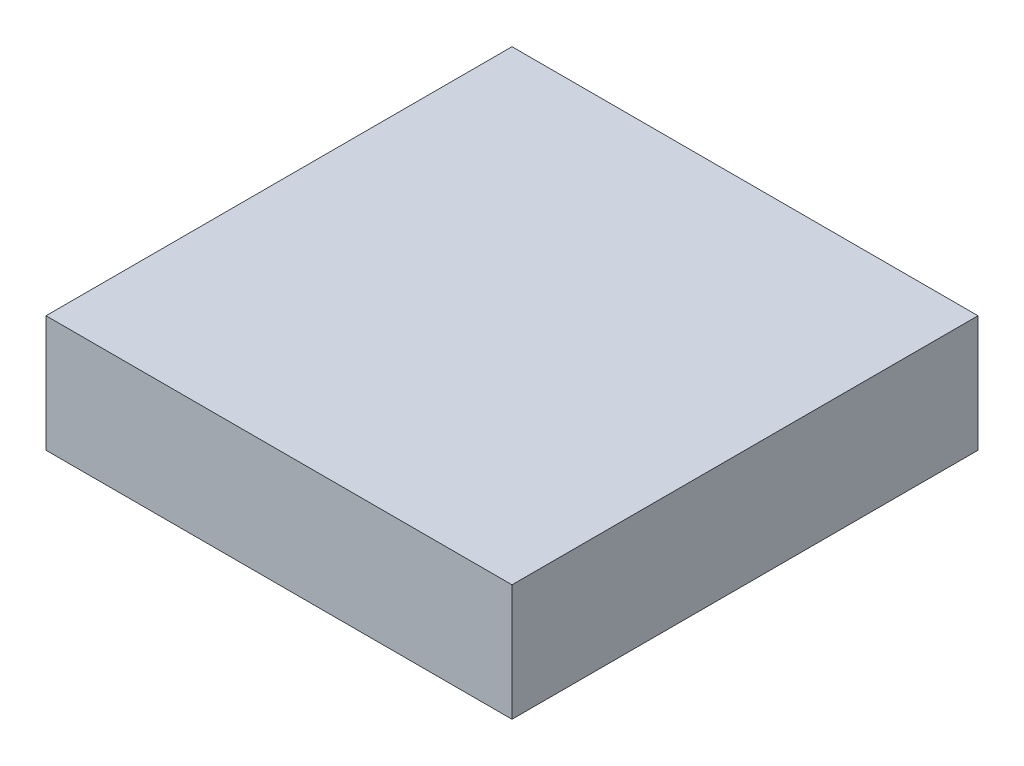
SolidWorks part; units mm, degrees
ref_plane "Front Plane" through (0, 0, 0) normal (0, 0, 1) x (1, 0, 0)
ref_plane "Top Plane" through (0, 0, 0) normal (0, 1, 0) x (1, 0, 0)
ref_plane "Right Plane" through (0, 0, 0) normal (1, 0, 0) x (0, 0, -1)
other "Configuration Table"
sketch "Sketch1" plane through (0, 0, 0) normal (0, 0, 1) x (1, 0, 0)
  line L1 (330, 1080) -> (370, 1080)
  line L2 (330, 1080) -> (330, 1090)
  line L3 (330, 1090) -> (370, 1090)
  line L4 (370, 1080) -> (370, 1090)
extrude "OVEN_sprey_nozul_tutucu_1" add sketch "Sketch1" against normal blind 40 from offset 220 separate body
